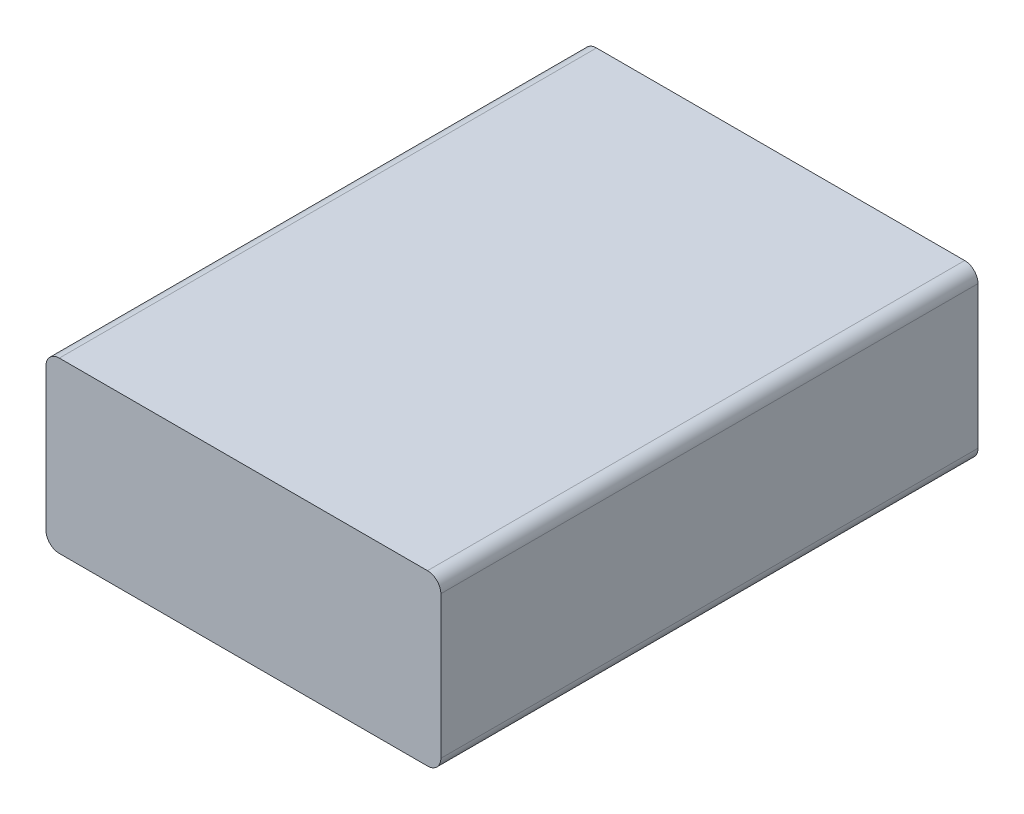
SolidWorks part; units mm, degrees
material "Pine"
ref_plane "Front Plane" through (0, 0, 0) normal (0, 0, 1) x (1, 0, 0)
ref_plane "Top Plane" through (0, 0, 0) normal (0, 1, 0) x (1, 0, 0)
ref_plane "Right Plane" through (0, 0, 0) normal (1, 0, 0) x (0, 0, -1)
sketch "Sketch1" plane through (0, 0, 0) normal (0, 0, 1) x (1, 0, 0)
  line L1 (41.45, -19.05) -> (-41.45, -19.05)
  line L2 (44.45, -16.05) -> (44.45, 16.05)
  line L3 (41.45, 19.05) -> (-41.45, 19.05)
  line L4 (-44.45, -16.05) -> (-44.45, 16.05)
  line L5 (44.45, -19.05) -> (-44.45, 19.05) construction
  line L6 (44.45, 19.05) -> (-44.45, -19.05) construction
  arc A0 (-41.45, -19.05) -> (-44.45, -16.05) centre (-41.45, -16.05) cw
  arc A1 (-41.45, 19.05) -> (-44.45, 16.05) centre (-41.45, 16.05) ccw
  arc A2 (44.45, 16.05) -> (41.45, 19.05) centre (41.45, 16.05) ccw
  arc A3 (41.45, -19.05) -> (44.45, -16.05) centre (41.45, -16.05) ccw
  point P0 (0, 0)
  dimension "D3" = 3
  dimension "D1" = 88.9
  dimension "D2" = 38.1
extrude "Boss-Extrude1" add sketch "Sketch1" along normal blind 120.95
equation "\"ChainSeperation\"= 80"
